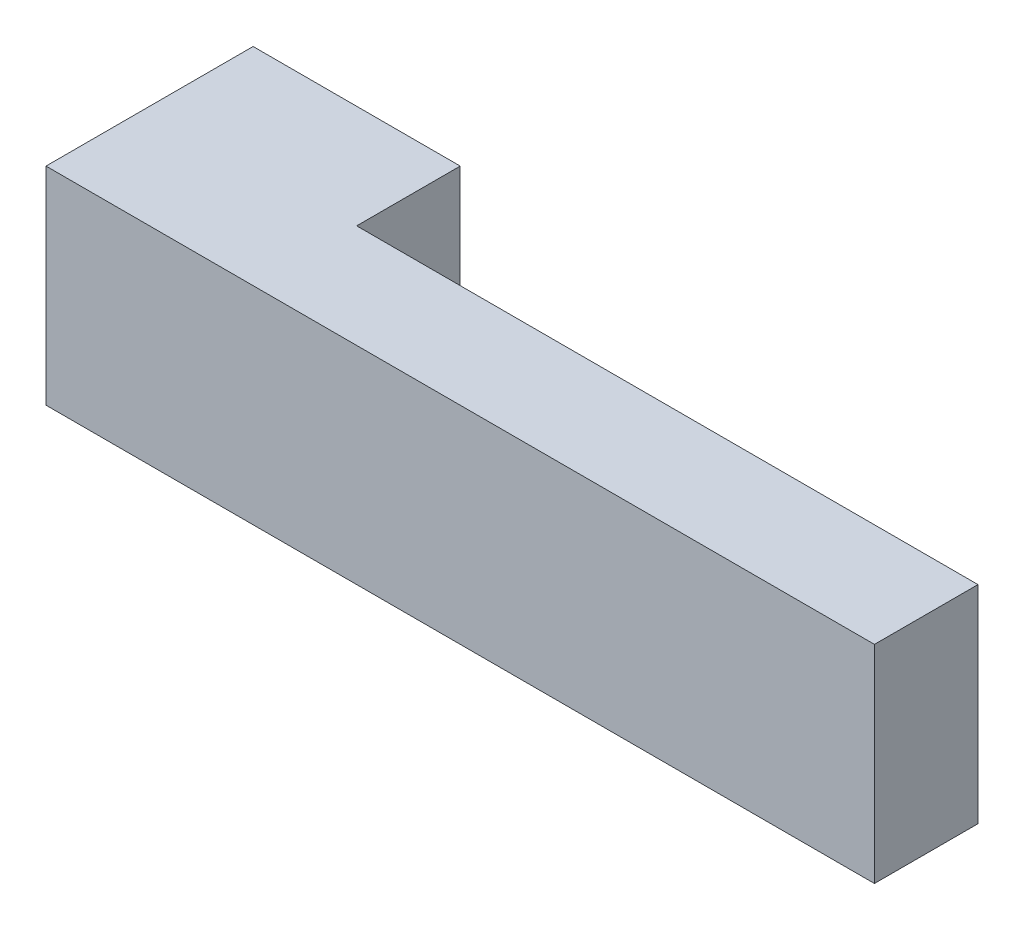
SolidWorks part; units mm, degrees
ref_plane "Přední rovina" through (0, 0, 0) normal (0, 0, 1) x (1, 0, 0)
ref_plane "Horní rovina" through (0, 0, 0) normal (0, 1, 0) x (1, 0, 0)
ref_plane "Pravá rovina" through (0, 0, 0) normal (1, 0, 0) x (0, 0, -1)
sketch "Sketch2" plane through (0, 0, 0) normal (0, 1, 0) x (1, 0, 0)
  line L0 (0, -20) -> (0, 0)
  line L1 (80, -20) -> (0, -20)
  line L2 (80, -20) -> (80, -10)
  line L3 (80, -10) -> (20, -10)
  line L7 (0, 0) -> (20, 0)
  line L8 (20, -10) -> (20, 0)
  dimension "D1" = 80
  dimension "D2" = 10
  dimension "D3" = 10
  dimension "D4" = 20
extrude "Boss-Extrude1" add sketch "Sketch2" along normal blind 20
